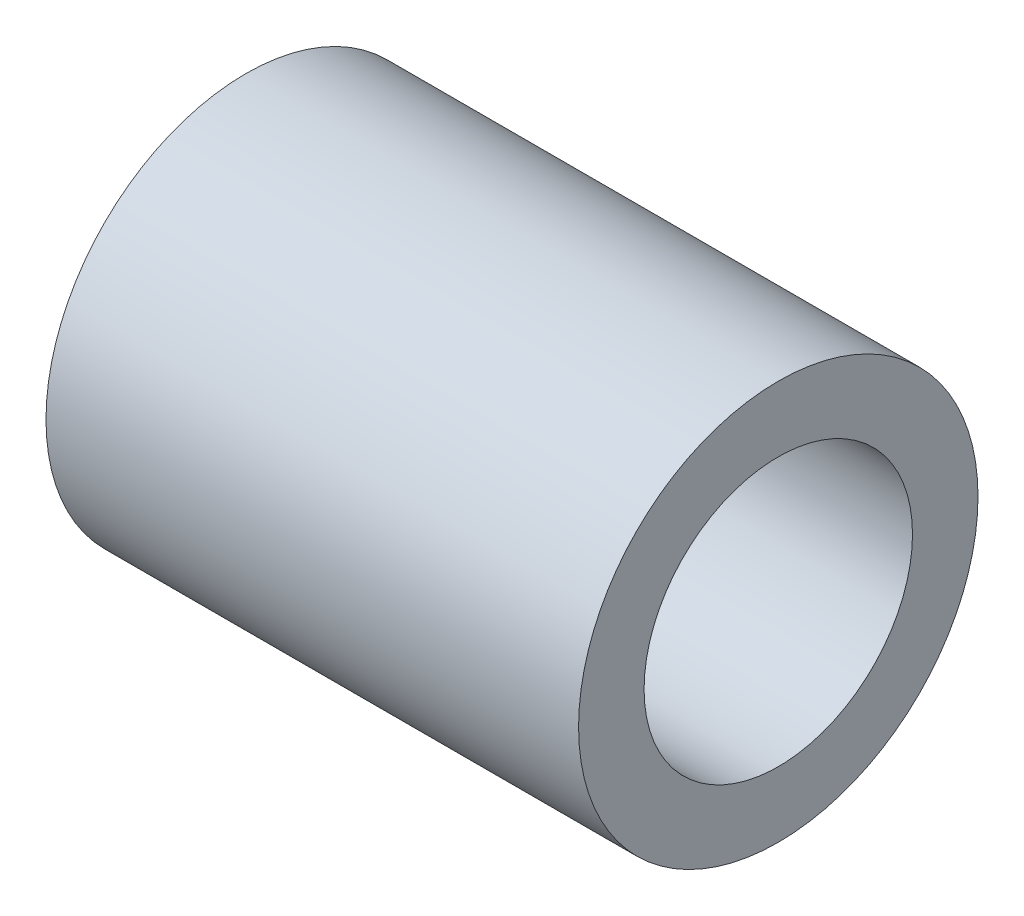
SolidWorks part; units mm, degrees
ref_plane "Front Plane" through (0, 0, 0) normal (0, 0, 1) x (1, 0, 0)
ref_plane "Top Plane" through (0, 0, 0) normal (0, 1, 0) x (1, 0, 0)
ref_plane "Right Plane" through (0, 0, 0) normal (1, 0, 0) x (0, 0, -1)
sketch "Sketch1" plane through (0, 0, 0) normal (1, 0, 0) x (0, 0, -1)
  circle A0 centre (0, 0) radius 4.7625
  dimension "D1" = 9.525
extrude "Boss-Extrude1" add sketch "Sketch1" along normal blind 12.7
sketch "Sketch2" plane through (0, 0, 0) normal (-1, 0, 0) x (0, 0, 1)
  circle A0 centre (0, 0) radius 3.2004
  dimension "D1" = 6.4008
extrude "Cut-Extrude1" cut sketch "Sketch2" against normal blind 15.875
